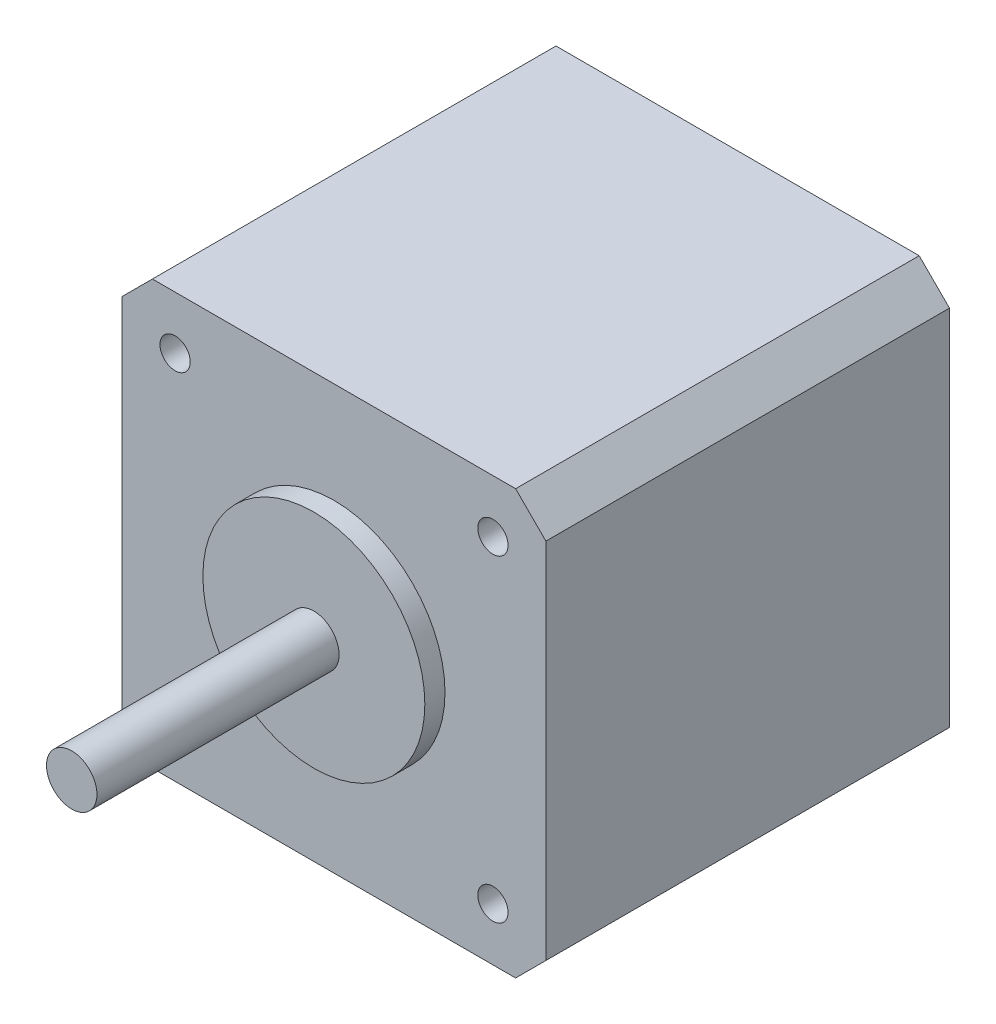
SolidWorks part; units mm, degrees
ref_plane "Front Plane" through (0, 0, 0) normal (0, 0, 1) x (1, 0, 0)
ref_plane "Top Plane" through (0, 0, 0) normal (0, 1, 0) x (1, 0, 0)
ref_plane "Right Plane" through (0, 0, 0) normal (1, 0, 0) x (0, 0, -1)
sketch "Sketch1" plane through (0, 0, 0) normal (0, 0, 1) x (1, 0, 0)
  line L1 (-21, 21) -> (21, 21)
  line L2 (-21, 21) -> (-21, -21)
  line L3 (-21, -21) -> (21, -21)
  line L4 (21, 21) -> (21, -21)
  line L5 (-21, 21) -> (21, -21) construction
  line L6 (-21, -21) -> (21, 21) construction
  point P0 (0, 0)
  dimension "D1" = 42
  dimension "D2" = 42
extrude "Boss-Extrude1" add sketch "Sketch1" along normal blind 40
sketch "Sketch2" plane through (0, 0, 40) normal (0, 0, 1) x (1, 0, 0)
  circle A0 centre (0, 0) radius 11
extrude "Boss-Extrude2" add sketch "Sketch2" along normal blind 2
sketch "Sketch3" plane through (0, 0, 42) normal (0, 0, 1) x (1, 0, 0)
  circle A0 centre (0, 0) radius 2.5
extrude "Boss-Extrude3" add sketch "Sketch3" along normal blind 24
chamfer "Chamfer1" distance 3 angle 45 4 edges at (-21, -21, 20) (21, -21, 20) (21, 21, 20) (-21, 21, 20)
sketch "Sketch4" plane through (0, 0, 40) normal (0, 0, 1) x (1, 0, 0)
  line L1 (-15.75, -15.75) -> (15.75, -15.75) construction
  line L2 (-15.75, -15.75) -> (-15.75, 15.75) construction
  line L3 (-15.75, 15.75) -> (15.75, 15.75) construction
  line L4 (15.75, -15.75) -> (15.75, 15.75) construction
  line L5 (-15.75, -15.75) -> (15.75, 15.75) construction
  line L6 (-15.75, 15.75) -> (15.75, -15.75) construction
  circle A0 centre (-15.75, 15.75) radius 1.5
  circle A1 centre (15.75, 15.75) radius 1.5
  circle A2 centre (-15.75, -15.75) radius 1.5
  circle A3 centre (15.75, -15.75) radius 1.5
  point P0 (0, 0)
  dimension "D1" = 31.5
  dimension "D2" = 31.5
extrude "Cut-Extrude1" cut sketch "Sketch4" against normal blind 10
